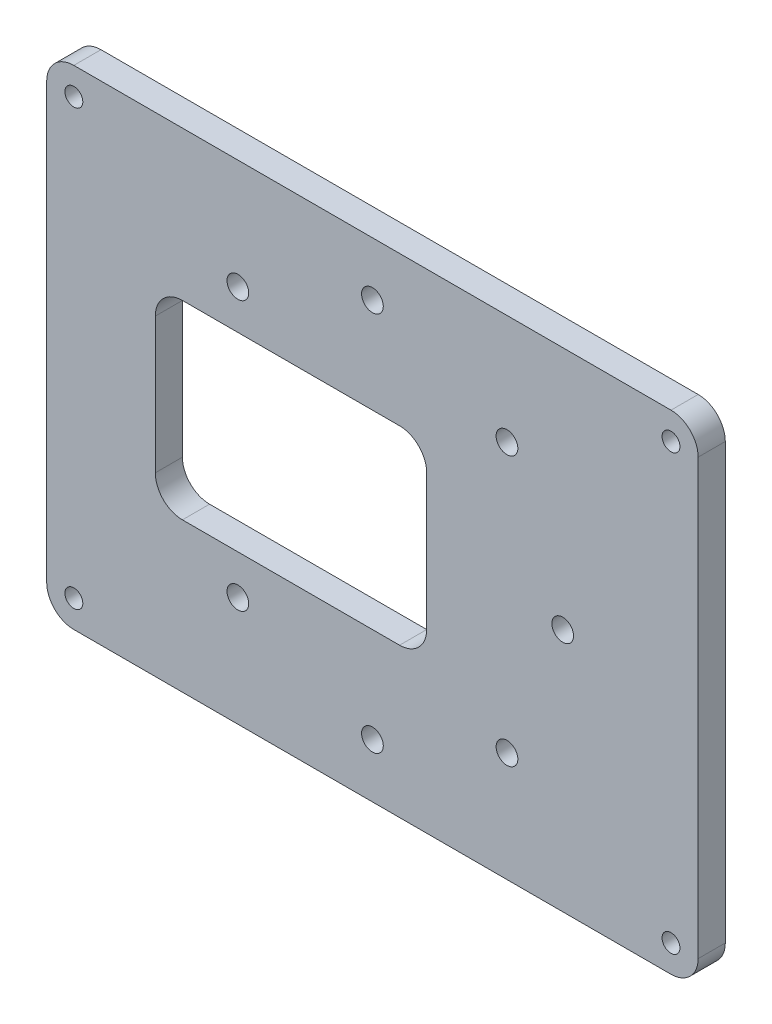
SolidWorks part; units mm, degrees
ref_plane "前视基准面" through (0, 0, 0) normal (0, 0, 1) x (1, 0, 0)
ref_plane "上视基准面" through (0, 0, 0) normal (0, 1, 0) x (1, 0, 0)
ref_plane "右视基准面" through (0, 0, 0) normal (1, 0, 0) x (0, 0, -1)
sketch "草图1" plane through (0, 0, 0) normal (0, 0, 1) x (1, 0, 0)
  line L1 (0, 0) -> (-120, 0)
  line L2 (0, 0) -> (0, -90)
  line L3 (0, -90) -> (-120, -90)
  line L4 (-120, 0) -> (-120, -90)
  line L5 (-115, -5) -> (-5, -5) construction
  line L6 (-115, -5) -> (-115, -85) construction
  line L7 (-115, -85) -> (-5, -85) construction
  line L8 (-5, -5) -> (-5, -85) construction
  line L9 (-100, -27.5) -> (-50, -27.5)
  line L10 (-100, -27.5) -> (-100, -62.5)
  line L11 (-100, -62.5) -> (-50, -62.5)
  line L12 (-50, -27.5) -> (-50, -62.5)
  circle A0 centre (-115, -85) radius 1.65
  circle A1 centre (-5, -85) radius 1.65
  circle A2 centre (-5, -5) radius 1.65
  circle A3 centre (-115, -5) radius 1.65
  circle A4 centre (-60, -45) radius 35.05 construction
  circle A5 centre (-24.95, -45) radius 2
  circle A6 centre (-35.2159, -69.7841) radius 2
  circle A7 centre (-60, -80.05) radius 2
  circle A8 centre (-84.7841, -69.7841) radius 2
  circle A10 centre (-84.7841, -20.2159) radius 2
  circle A11 centre (-60, -9.95) radius 2
  circle A12 centre (-35.2159, -20.2159) radius 2
  circle A13 centre (-95.05, -45) radius 2 [skipped]
  point P33 (-60, -45)
  dimension "D7" = 3.3
  dimension "D8" = 3.3
  dimension "D9" = 3.3
  dimension "D10" = 3.3
  dimension "D11" = 70.1
  dimension "D14" = 4
  dimension "D1" = 120
  dimension "D2" = 90
  dimension "D3" = 110
  dimension "D4" = 80
  dimension "D5" = 5
  dimension "D6" = 5
  dimension "D12" = 45
  dimension "D13" = 60
  dimension "D16" = 35
  dimension "D17" = 50
  dimension "D18" = 27.5
  dimension "D19" = 20
  dimension "D15" = 8
extrude "凸台-拉伸1" add sketch "草图1" along normal blind 5
fillet "圆角1" radius 5 4 edges at (0, -90, 2.5) (-120, -90, 2.5) (-120, 0, 2.5) (0, 0, 2.5)
fillet "圆角2" radius 5 4 edges at (-100, -62.5, 2.5) (-50, -62.5, 2.5) (-50, -27.5, 2.5) (-100, -27.5, 2.5)
